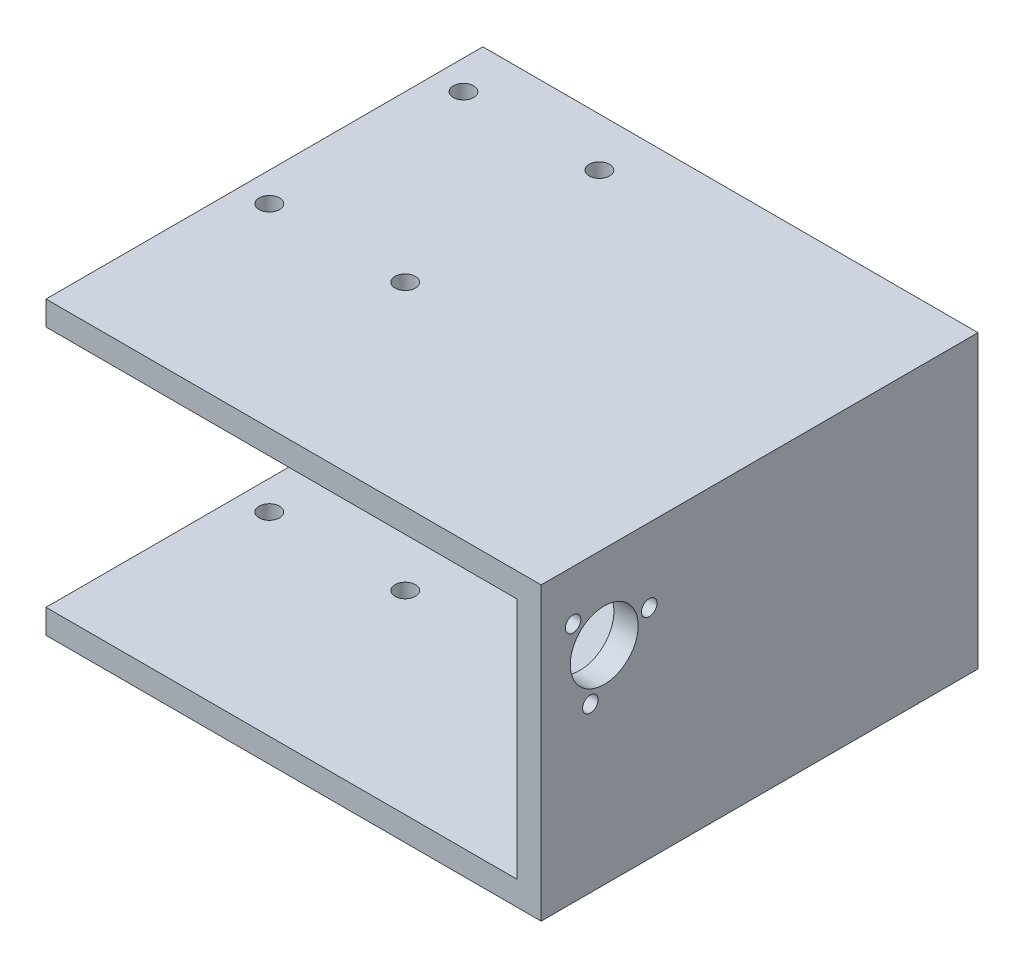
SolidWorks part; units mm, degrees
ref_plane "前视基准面" through (0, 0, 0) normal (0, 0, 1) x (1, 0, 0)
ref_plane "上视基准面" through (0, 0, 0) normal (0, 1, 0) x (1, 0, 0)
ref_plane "右视基准面" through (0, 0, 0) normal (1, 0, 0) x (0, 0, -1)
other "Configuration Table"
sketch "草图1" plane through (0, 0, 0) normal (0, 0, 1) x (1, 0, 0)
  line L0 (0, 0) -> (0, 5)
  line L1 (0, 5) -> (102, 5)
  line L2 (102, 5) -> (102, -55)
  line L3 (102, -55) -> (0, -55)
  line L4 (0, -55) -> (0, -50)
  line L5 (0, -50) -> (97, -50)
  line L6 (97, -50) -> (97, 0)
  line L7 (97, 0) -> (0, 0)
  dimension "D1" = 5
  dimension "D2" = 97
  dimension "D3" = 5
  dimension "D4" = 5
  dimension "D5" = 50
extrude "凸台-拉伸1" add sketch "草图1" along normal blind 90 contours L5 L6 L7 L0 L1 L2 L3 L4
sketch "Sketch1" plane through (0, 0, 0) normal (0, 1, 0) x (1, 0, 0)
  line L0 (0, -90) -> (0, 0) construction
  line L1 (6, -10) -> (34, -10) construction
  line L2 (6, -10) -> (6, -50) construction
  line L3 (6, -50) -> (34, -50) construction
  line L4 (34, -10) -> (34, -50) construction
  line L5 (0, 0) -> (102, -90) construction
  line L6 (102, 0) -> (0, -90) construction
  line L7 (51, -45) -> (87.6415, -45) construction
  line L8 (0, 0) -> (102, 0) construction
  circle A0 centre (6, -10) radius 2.1
  circle A1 centre (34, -10) radius 2.1
  circle A2 centre (34, -50) radius 2.1
  circle A3 centre (6, -50) radius 2.1
  point P18 (51, -45)
  dimension "D5" = 4.2
  dimension "D6" = 4.2
  dimension "D7" = 4.2
  dimension "D8" = 4.2
  dimension "D1" = 6
  dimension "D2" = 28
  dimension "D3" = 40
  dimension "D4" = 10
extrude "Cut-Extrude1" cut sketch "Sketch1" along normal through all both and the other way through all
sketch "草图2" plane through (97, 0, 0) normal (-1, 0, 0) x (0, 0, 1)
  line L0 (90, 0) -> (0, 0) construction
  line L1 (90, -50) -> (90, 0) construction
  circle A0 centre (77, -12.25) radius 12.25
  circle A1 centre (77, -12.25) radius 7
  dimension "D1" = 24.5
  dimension "D2" = 14
  dimension "D3" = 12.25
  dimension "D4" = 13
extrude "切除-拉伸1" cut sketch "草图2" against normal blind 10 contours A1
sketch "草图6" plane through (102, 0, 0) normal (1, 0, 0) x (0, 0, -1)
  circle A0 centre (-83.4216, -5.2491) radius 1.6
  circle A1 centre (-35.7469, -21.963) radius 1.25 construction
  circle A2 centre (-35.7469, -21.963) radius 1.25 construction
  circle A3 centre (-83.4216, -5.2491) radius 1.25 construction
  circle A4 centre (-83.4216, -5.2491) radius 1.25
  dimension "D1" = 3.2
extrude "切除-拉伸3" cut sketch "草图6" against normal blind 10 contours A0
pattern_circular "阵列(圆周)1" count 3 over 360 about axis through (0, -12.25, 77) along (1, 0, 0) of "切除-拉伸3"
